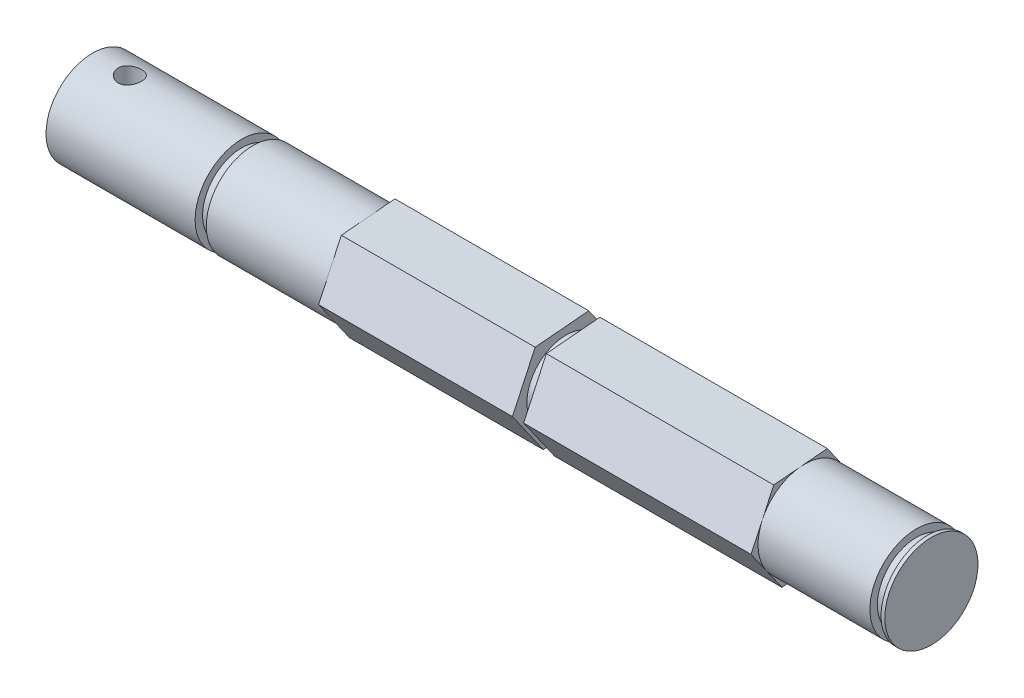
SolidWorks part; units mm, degrees
material "Plain Carbon Steel"
ref_plane "Front Plane" through (0, 0, 0) normal (0, 0, 1) x (1, 0, 0)
ref_plane "Top Plane" through (0, 0, 0) normal (0, 1, 0) x (1, 0, 0)
ref_plane "Right Plane" through (0, 0, 0) normal (1, 0, 0) x (0, 0, -1)
sketch "Sketch1" plane through (0, 0, 0) normal (1, 0, 0) x (0, 0, -1)
  line L1 (2.105, -3.0016) -> (3.652, 0.3222)
  line L2 (3.652, 0.3222) -> (1.547, 3.3238)
  line L3 (1.547, 3.3238) -> (-2.105, 3.0016)
  line L4 (-2.105, 3.0016) -> (-3.652, -0.3222)
  line L5 (-3.652, -0.3222) -> (-1.547, -3.3238)
  line L6 (-1.547, -3.3238) -> (2.105, -3.0016)
  circle A0 centre (0, 0) radius 3.175 construction
  dimension "D1" = 6.35
extrude "Boss-Extrude1" add sketch "Sketch1" along normal blind 38.1
sketch "Sketch2" plane through (38.1, 0, 0) normal (1, 0, 0) x (0, 0, -1)
  circle A0 centre (0, 0) radius 3.175
  dimension "D1" = 6.35
sketch "Sketch3" plane through (0, 0, 0) normal (-1, 0, 0) x (0, 0, 1)
  circle A0 centre (0, 0) radius 3.175
  dimension "D1" = 6.35
extrude "Boss-Extrude3" add sketch "Sketch3" along normal blind 19.05
sketch "Sketch4" plane through (0, 0, 0) normal (0, 1, 0) x (1, 0, 0)
  line L0 (-19.05, 3.175) -> (-19.05, -3.175) construction
  circle A0 centre (-16.51, 0) radius 0.7937
  dimension "D2" = 1.5875
  dimension "D1" = 2.54
extrude "Cut-Extrude1" cut sketch "Sketch4" along normal through all and the other way through all
sketch "Sketch5" plane through (38.1, 0, 0) normal (1, 0, 0) x (0, 0, -1)
  circle A0 centre (0, 0) radius 3.6662
  circle A1 centre (0, 0) radius 3.175
  line M2 (-1.547, -3.3238) -> (2.105, -3.0016)
  line M3 (2.105, -3.0016) -> (3.652, 0.3222)
  line M4 (3.652, 0.3222) -> (1.547, 3.3238)
  line M5 (1.547, 3.3238) -> (-2.105, 3.0016)
  line M6 (-2.105, 3.0016) -> (-3.652, -0.3222)
  line M7 (-3.652, -0.3222) -> (-1.547, -3.3238)
extrude "Cut-Extrude4" cut sketch "Sketch5" against normal blind 8.636 contours A0 M6 | A1 M6 M7 | A0 M7 | A1 M7 M2 | A0 M2 | A1 M2 M3 | A0 M3 | A1 M3 M4 | A0 M4 | A1 M4 M5 | A0 M5 | A1 M5 M6
ref_plane "Plane1" through (37.084, 0, 0) normal (1, 0, 0) x (0, 0, -1)
sketch "Sketch6" plane through (37.084, 0, 0) normal (1, 0, 0) x (0, 0, -1)
  circle A0 centre (0, 0) radius 2.667
  dimension "D1" = 5.334
extrude "Cut-Extrude5" cut sketch "Sketch6" along normal blind 0.762 flip side to cut
ref_plane "Plane2" through (-8.128, 0, 0) normal (-1, 0, 0) x (0, 0, 1)
sketch "Sketch9" plane through (-8.128, 0, 0) normal (-1, 0, 0) x (0, 0, 1)
  circle A0 centre (0, 0) radius 2.667
  dimension "D1" = 5.334
extrude "Cut-Extrude6" cut sketch "Sketch9" along normal blind 0.762 flip side to cut
ref_plane "Plane3" through (13.97, 0, 0) normal (-1, 0, 0) x (0, 0, 1)
sketch "Sketch10" plane through (13.97, 0, 0) normal (-1, 0, 0) x (0, 0, 1)
  circle A0 centre (0, 0) radius 2.667
  dimension "D1" = 5.334
extrude "Cut-Extrude7" cut sketch "Sketch10" along normal blind 0.762 flip side to cut
